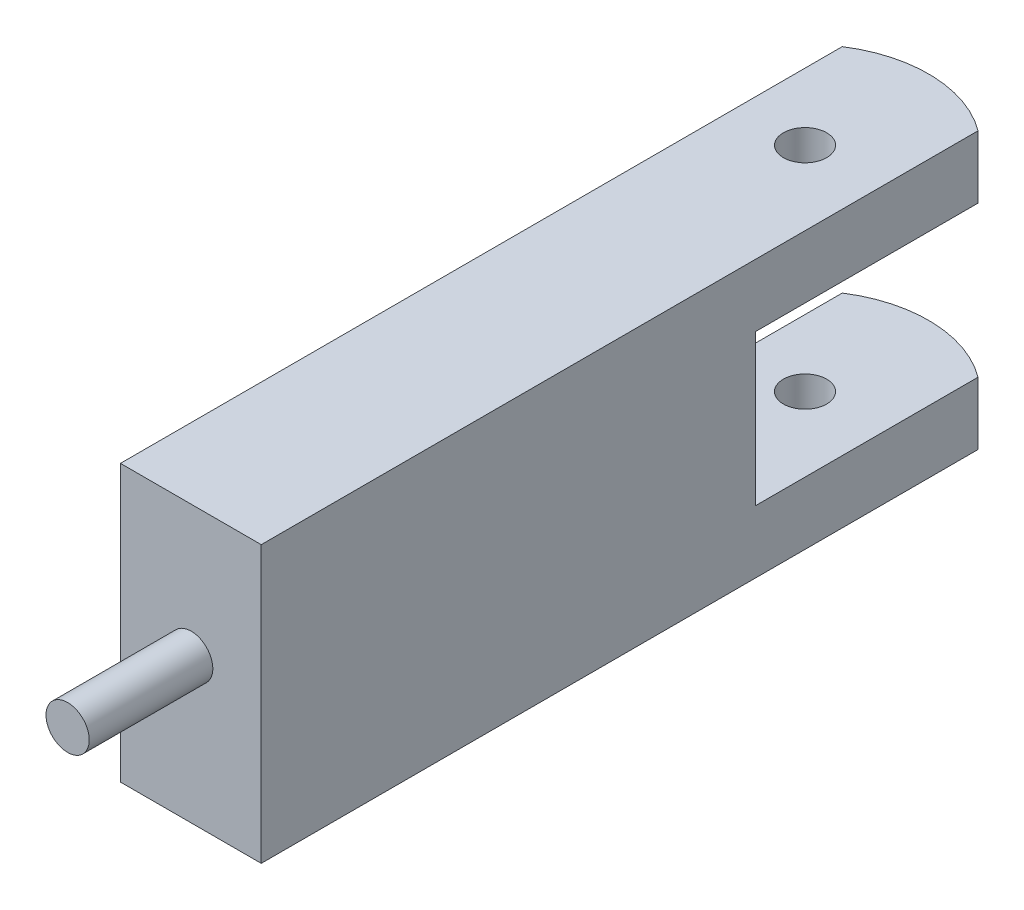
SolidWorks part; units mm, degrees
ref_plane "Front Plane" through (0, 0, 0) normal (0, 0, 1) x (1, 0, 0)
ref_plane "Top Plane" through (0, 0, 0) normal (0, 1, 0) x (1, 0, 0)
ref_plane "Right Plane" through (0, 0, 0) normal (1, 0, 0) x (0, 0, -1)
sketch "Sketch3" plane through (0, 0, 0) normal (0, 0, 1) x (1, 0, 0)
  line L1 (0, 0) -> (30, 0)
  line L2 (0, 0) -> (0, 30)
  line L3 (0, 30) -> (30, 30)
  line L4 (30, 0) -> (30, 30)
  dimension "D1" = 30
  dimension "D2" = 30
extrude "Boss-Extrude1" add sketch "Sketch3" along normal blind 40
ref_plane "Plane1" through (0, 15, 0) normal (0, -1, 0) x (-1, 0, 0)
sketch "Sketch8" plane through (0, 0, 0) normal (0, 0, -1) x (-1, 0, 0)
  line L0 (-30, 17.573) -> (-21.5266, 30)
  line L1 (-30, 0) -> (-30, 30) construction
  line L2 (-30, 30) -> (0, 30) construction
extrude "Cut-Extrude4" cut sketch "Sketch8" against normal blind 40 and the other way through all
ref_plane "Plane2" through (15, 0, 0) normal (-1, 0, 0) x (0, 0, 1)
mirror "Mirror4" about plane through (15, 0, 0) normal (-1, 0, 0) of "Cut-Extrude4"
mirror "Mirror5" about plane through (0, 15, 0) normal (0, -1, 0) of "Mirror4", "Cut-Extrude4"
sketch "Sketch9" plane through (0, 0, 0) normal (0, 1, 0) x (1, 0, 0)
  line L0 (15, 2.8303) -> (15, -2.8303) construction
  line L1 (21.5266, 0) -> (8.4734, 0) construction
  line L2 (0, 0) -> (5.7692, 13.8462)
  line L3 (30, 0) -> (22.4742, 16.6435)
  line L4 (0, 0) -> (30, 0)
  arc A0 (24.9248, 11.2239) -> (5.7692, 13.8462) centre (15, 10) ccw
  circle A1 centre (15, 10) radius 1.75
  dimension "D1" = 20
  dimension "D2" = 3.5
extrude "Boss-Extrude2" add sketch "Sketch9" along normal blind 30 contours L3 A0 L2 L4 A1
sketch "Sketch10" plane through (0, 0, 0) normal (0, 0, 1) x (1, 0, 0)
  line L0 (0, 17.573) -> (8.4734, 30)
  line L1 (8.4734, 30) -> (0, 30)
  line L2 (0, 30) -> (0, 17.573)
  line L3 (8.4734, 0) -> (0, 0)
  line L4 (0, 0) -> (0, 12.427)
  line L5 (0, 12.427) -> (8.4734, 0)
  line L6 (21.5266, 0) -> (30, 12.427)
  line L7 (30, 12.427) -> (30, 0)
  line L8 (30, 0) -> (21.5266, 0)
  line L9 (30, 17.573) -> (21.5266, 30)
  line L10 (21.5266, 30) -> (30, 30)
  line L11 (30, 30) -> (30, 17.573)
extrude "Cut-Extrude5" cut sketch "Sketch10" against normal blind 30
sketch "Sketch11" plane through (30, 0, 0) normal (1, 0, 0) x (0, 0, -1)
  line L8 (-40, 30) -> (-40, 0)
  line L10 (20, 0) -> (20, 30) construction
  line L11 (0, 21.1) -> (20, 21.1)
  line L12 (0, 21.1) -> (0, 8.9)
  line L13 (0, 8.9) -> (20, 8.9)
  line L14 (20, 21.1) -> (20, 8.9)
  line L15 (17.5765, 30) -> (-40, 30) construction
  dimension "D1" = 0
  dimension "D2" = 8.9
  dimension "D3" = 12.2
  dimension "D4" = 20
extrude "Cut-Extrude6" cut sketch "Sketch11" against normal mid plane 89 contours L14 L11 L12 L13
sketch "Sketch12" plane through (0, 0, 40) normal (0, 0, 1) x (1, 0, 0)
  circle A0 centre (15.3218, 15.5201) radius 1.75
  point P2 (15.3218, 15.5201)
  dimension "D1" = 3.5
extrude "Boss-Extrude3" add sketch "Sketch12" along normal blind 10 contours A0
sketch "Sketch13" plane through (0, 0, 40) normal (0, 0, 1) x (1, 0, 0)
sketch "Sketch14" plane through (0, 0, 40) normal (0, 0, 1) x (1, 0, 0)
sketch "Sketch15" plane through (0, 0, 40) normal (0, 0, 1) x (1, 0, 0)
  line L1 (-0.6554, 35.1011) -> (-0.6554, 26.1696)
  line L2 (0, 15) -> (35.3241, 15) construction
  line L10 (-0.6554, 26.1696) -> (30.3833, 26.1696)
  line L11 (30.3833, 26.1696) -> (30.3833, 35.1011)
  line L12 (30.3833, 35.1011) -> (-0.6554, 35.1011)
  line L14 (-0.6554, 35.1011) -> (0, 35.1011)
  line L15 (0, 17.573) -> (0, 12.427) construction
  line L16 (30.3833, -5.1011) -> (-0.6554, -5.1011)
  line L17 (30.3833, 3.8304) -> (30.3833, -5.1011)
  line L18 (-0.6554, 3.8304) -> (30.3833, 3.8304)
  line L19 (-0.6554, -5.1011) -> (-0.6554, 3.8304)
  line L20 (5.8616, 26.1696) -> (5.7692, 3.9659)
  line L21 (0, 17.573) -> (8.4734, 30) construction
  line L22 (5.7692, 3.9659) -> (-0.6554, 3.8304)
  line L23 (-0.6554, 26.1696) -> (-0.6554, 3.8304)
  line L24 (30.3833, 26.1696) -> (30.3833, 3.8304)
  line L25 (24.2208, 3.8304) -> (24.2208, 26.1696)
  line M10 (21.5266, 0) -> (30, 12.427)
  line M11 (30, 12.427) -> (30, 17.573)
  line M12 (30, 17.573) -> (21.5266, 30)
  line M13 (21.5266, 30) -> (8.4734, 30)
  line M14 (8.4734, 30) -> (0, 17.573)
  line M15 (0, 17.573) -> (0, 12.427)
  line M16 (0, 12.427) -> (8.4734, 0)
  line M17 (8.4734, 0) -> (21.5266, 0)
extrude "Cut-Extrude13" cut sketch "Sketch15" against normal blind 67 contours L10 M14 M12 M13 | L25 L2 M11 M12 | L2 L25 M10 M11 | L18 M16 M17 M10 | L2 L20 M15 M16 | L2 L20 M15 M14
sketch "Sketch16" plane through (0, 0, 40) normal (0, 0, 1) x (1, 0, 0)
  line L0 (9.5969, 26.1696) -> (9.5969, 3.8304)
  line L1 (5.8616, 26.1696) -> (24.1384, 26.1696) construction
  line L2 (5.8616, 3.8304) -> (24.1384, 3.8304) construction
  line L4 (20.9913, 3.8304) -> (20.9913, 26.1696)
  line L6 (9.5969, 26.1696) -> (3.1137, 26.1696)
  line L7 (3.1137, 26.1696) -> (3.1137, 3.8304)
  line L8 (3.1137, 3.8304) -> (9.5969, 3.8304)
  line L9 (20.9913, 26.1696) -> (28.1247, 26.1696)
  line L10 (28.1247, 26.1696) -> (28.1247, 3.8304)
  line L11 (28.1247, 3.8304) -> (20.9913, 3.8304)
extrude "Cut-Extrude14" cut sketch "Sketch16" against normal blind 67
